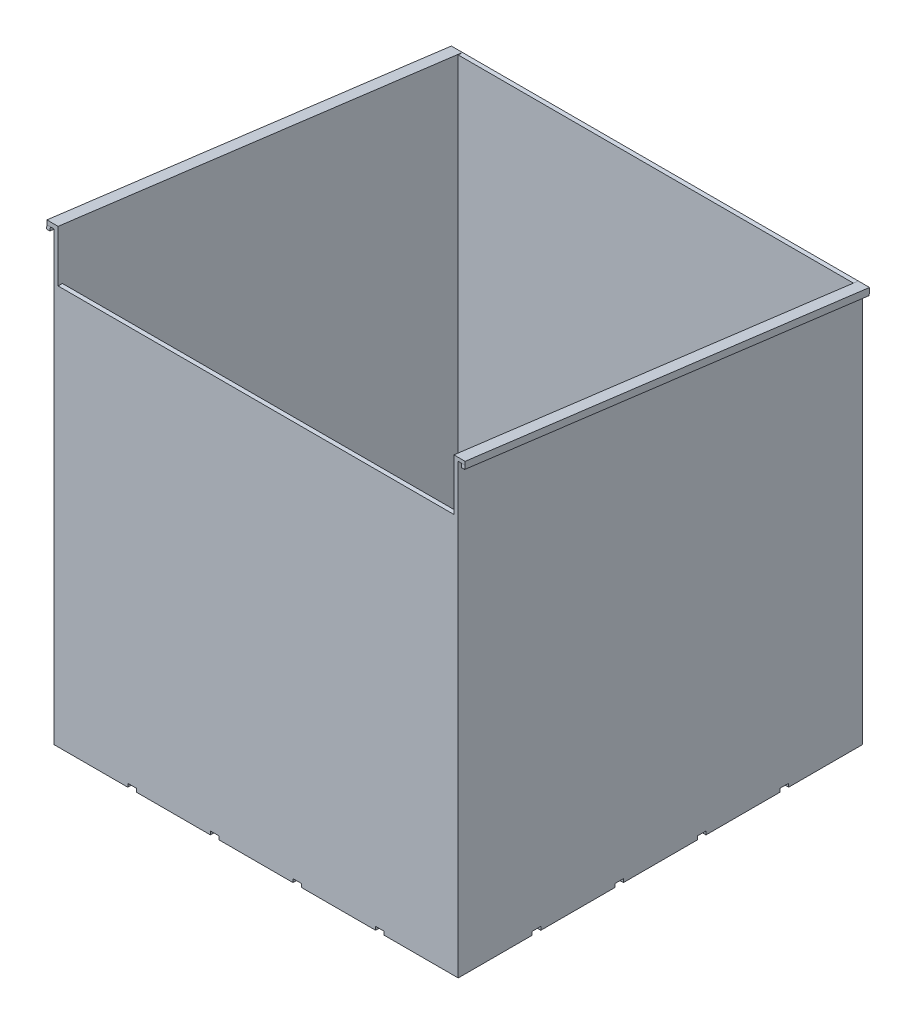
SolidWorks part; units mm, degrees
ref_plane "Front Plane" through (0, 0, 0) normal (0, 0, 1) x (1, 0, 0)
ref_plane "Top Plane" through (0, 0, 0) normal (0, 1, 0) x (1, 0, 0)
ref_plane "Right Plane" through (0, 0, 0) normal (1, 0, 0) x (0, 0, -1)
sketch "Sketch1" plane through (0, 0, 0) normal (0, 1, 0) x (1, 0, 0)
  line L1 (0, 0) -> (230, 0)
  line L2 (0, 0) -> (0, 230)
  line L3 (0, 230) -> (230, 230)
  line L4 (230, 0) -> (230, 230)
  dimension "D1" = 230
  dimension "D2" = 230
extrude "Extrude-Thin1" add sketch "Sketch1" along normal blind 230 thin contours L2 L3 L4 L1
sketch "Sketch4" plane through (232.5, 0, 0) normal (1, 0, 0) x (0, 0, -1)
  line L0 (-2.5, 230) -> (-2.5, 260)
  line L1 (-2.5, 260) -> (232.5, 230)
  line L2 (232.5, 230) -> (-2.5, 230)
  dimension "D1" = 30
extrude "Boss-Extrude1" add sketch "Sketch4" against normal blind 2.5 contours L1 L2 L0
sketch "Sketch5" plane through (-2.5, 0, 0) normal (-1, 0, 0) x (0, 0, 1)
  line L3 (-232.5, 230) -> (2.5, 230)
  line L4 (2.5, 230) -> (2.5, 260)
  line L5 (2.5, 260) -> (-232.5, 230)
  dimension "D1" = 30
extrude "Boss-Extrude2" add sketch "Sketch5" against normal blind 2.5 contours L5 L3 L4
sketch "Sketch6" plane through (-2.5, 0, 0) normal (-1, 0, 0) x (0, 0, 1)
  line L0 (-232.5, 230) -> (2.5, 260)
  line L1 (2.5, 260) -> (2.5, 257.5)
  line L2 (2.5, 257.5) -> (2.5, 0) construction
  line L3 (2.5, 257.5) -> (-232.5, 227.5)
  line L4 (-232.5, 227.5) -> (-232.5, 0) construction
  line L5 (-232.5, 227.5) -> (-232.5, 230)
  dimension "D1" = 2.5
extrude "Boss-Extrude5" add sketch "Sketch6" along normal blind 4 contours L0 L1 L3 L5
sketch "Sketch8" plane through (0, 253.0568, -32.3051) normal (0, -0.9919, 0.1266) x (1, 0, 0)
  line L0 (-6.5, -201.8196) -> (-6.5, 35.0876)
  line L1 (-6.5, 35.0876) -> (-4.5, 35.0876)
  line L2 (-4.5, 35.0876) -> (-2.5, 35.0876) construction
  line L3 (-4.5, 35.0876) -> (-4.5, -201.8196)
  line L4 (-6.5, -201.8196) -> (-2.5, -201.8196) construction
  line L5 (-4.5, -201.8196) -> (-6.5, -201.8196)
extrude "Boss-Extrude6" add sketch "Sketch8" along normal blind 2 contours L0 L1 L3 L5
sketch "Sketch9" plane through (232.5, 0, 0) normal (1, 0, 0) x (0, 0, -1)
  line L0 (-2.5, 260) -> (232.5, 230)
  line L1 (232.5, 230) -> (232.5, 228)
  line L2 (232.5, 228) -> (232.5, 0) construction
  line L3 (232.5, 228) -> (-2.5, 258)
  line L4 (-2.5, 258) -> (-2.5, 0) construction
  line L5 (-2.5, 258) -> (-2.5, 260)
  dimension "D1" = 2
extrude "Boss-Extrude7" add sketch "Sketch9" along normal blind 4 contours L0 L1 L3 L5
sketch "Sketch10" plane through (0, 253.5488, -32.3679) normal (0, -0.9919, 0.1266) x (1, 0, 0)
  line L0 (236.5, 35.1509) -> (236.5, -201.7563)
  line L1 (236.5, -201.7563) -> (234.5, -201.7563)
  line L2 (236.5, -201.7563) -> (232.5, -201.7563) construction
  line L3 (234.5, -201.7563) -> (234.5, 35.1509)
  line L4 (234.5, 35.1509) -> (236.5, 35.1509)
extrude "Boss-Extrude8" add sketch "Sketch10" along normal blind 2
sketch "Sketch11" plane through (0, 253.5488, -32.3679) normal (0, -0.9919, 0.1266) x (1, 0, 0)
  line L0 (232.5, -201.7563) -> (234.5, -201.7563)
  line L1 (234.5, -201.7563) -> (234.5, -199.7563)
  line L2 (234.5, 35.1509) -> (234.5, -199.7563) construction
  line L3 (234.5, -199.7563) -> (232.5, -199.7563)
  line L4 (232.5, -199.7563) -> (232.5, 35.1509) construction
  line L5 (232.5, -199.7563) -> (232.5, -201.7563)
  dimension "D1" = 2
  dimension "D2" = 2
extrude "Boss-Extrude9" add sketch "Sketch11" along normal blind 2 contours L3 L5 L0 L1
sketch "Sketch12" plane through (0, 253.0568, -32.3051) normal (0, -0.9919, 0.1266) x (1, 0, 0)
  line L0 (-2.5, -201.8196) -> (-2.5, -199.8196)
  line L1 (-2.5, 35.0876) -> (-2.5, -199.8196) construction
  line L2 (-4.5, -201.8196) -> (-2.5, -201.8196) construction
  line L3 (-2.5, -199.8196) -> (-4.5, -199.8196)
  line L4 (-4.5, 35.0876) -> (-4.5, -199.8196) construction
  line L5 (-4.5, -199.8196) -> (-4.5, -201.8196)
  line L6 (-4.5, -201.8196) -> (-2.5, -201.8196)
  dimension "D1" = 2
  dimension "D2" = 2
extrude "Boss-Extrude10" add sketch "Sketch12" along normal blind 2 contours L6 L0 L3 L5
sketch "Sketch13" plane through (0, 0, 0) normal (0, -1, 0) x (1, 0, 0)
  line L0 (-2.5, 2.5) -> (40.5, 2.5)
  line L1 (-2.5, 2.5) -> (232.5, 2.5) construction
  line L2 (40.5, 2.5) -> (40.5, -4.3411)
  line L3 (40.5, -4.3411) -> (45.5, -4.3411)
  line L4 (45.5, -4.3411) -> (45.5, 2.5)
  line L5 (45.5, 2.5) -> (88.5, 2.5)
  line L6 (88.5, 2.5) -> (88.5, -4.3411)
  line L7 (88.5, -4.3411) -> (93.5, -4.3411)
  line L8 (93.5, -4.3411) -> (93.5, 2.5)
  line L9 (93.5, 2.5) -> (136.5, 2.5)
  line L10 (136.5, 2.5) -> (136.5, -4.3411)
  line L11 (136.5, -4.3411) -> (141.5, -4.3411)
  line L12 (141.5, -4.3411) -> (141.5, 2.5)
  line L13 (141.5, 2.5) -> (184.5, 2.5)
  line L14 (184.5, 2.5) -> (184.5, -4.3411)
  line L15 (184.5, -4.3411) -> (189.5, -4.3411)
  line L16 (189.5, -4.3411) -> (189.5, 2.5)
  line L17 (189.5, 2.5) -> (232.5, 2.5)
  line L18 (232.5, -232.5) -> (189.5, -232.5)
  line L19 (189.5, -232.5) -> (189.5, -225.6589)
  line L20 (189.5, -225.6589) -> (184.5, -225.6589)
  line L21 (184.5, -225.6589) -> (184.5, -232.5)
  line L22 (184.5, -232.5) -> (141.5, -232.5)
  line L23 (141.5, -232.5) -> (141.5, -225.6589)
  line L24 (141.5, -225.6589) -> (136.5, -225.6589)
  line L25 (136.5, -225.6589) -> (136.5, -232.5)
  line L26 (136.5, -232.5) -> (93.5, -232.5)
  line L27 (93.5, -232.5) -> (93.5, -225.6589)
  line L28 (93.5, -225.6589) -> (88.5, -225.6589)
  line L29 (88.5, -225.6589) -> (88.5, -232.5)
  line L30 (88.5, -232.5) -> (45.5, -232.5)
  line L31 (45.5, -232.5) -> (45.5, -225.6589)
  line L32 (45.5, -225.6589) -> (40.5, -225.6589)
  line L33 (40.5, -225.6589) -> (40.5, -232.5)
  line L34 (40.5, -232.5) -> (-2.5, -232.5)
  line L35 (-2.5, -232.5) -> (232.5, -232.5) construction
  line L36 (232.5, 2.5) -> (232.5, -232.5) construction
  line L37 (-2.5, -232.5) -> (-2.5, -189.5)
  line L38 (-2.5, -189.5) -> (4.3411, -189.5)
  line L39 (4.3411, -189.5) -> (4.3411, -184.5)
  line L40 (4.3411, -184.5) -> (-2.5, -184.5)
  line L41 (-2.5, -184.5) -> (-2.5, -141.5)
  line L42 (-2.5, -141.5) -> (4.3411, -141.5)
  line L43 (4.3411, -141.5) -> (4.3411, -136.5)
  line L44 (4.3411, -136.5) -> (-2.5, -136.5)
  line L45 (-2.5, -136.5) -> (-2.5, -93.5)
  line L46 (-2.5, -93.5) -> (4.3411, -93.5)
  line L47 (4.3411, -93.5) -> (4.3411, -88.5)
  line L48 (4.3411, -88.5) -> (-2.5, -88.5)
  line L49 (-2.5, -88.5) -> (-2.5, -45.5)
  line L50 (-2.5, -45.5) -> (4.3411, -45.5)
  line L51 (4.3411, -45.5) -> (4.3411, -40.5)
  line L52 (4.3411, -40.5) -> (-2.5, -40.5)
  line L53 (-2.5, -40.5) -> (-2.5, 2.5)
  line L54 (232.5, 2.5) -> (232.5, -40.5)
  line L55 (232.5, -40.5) -> (225.6589, -40.5)
  line L56 (225.6589, -40.5) -> (225.6589, -45.5)
  line L57 (225.6589, -45.5) -> (232.5, -45.5)
  line L58 (232.5, -45.5) -> (232.5, -88.5)
  line L59 (232.5, -88.5) -> (225.6589, -88.5)
  line L60 (225.6589, -88.5) -> (225.6589, -93.5)
  line L61 (225.6589, -93.5) -> (232.5, -93.5)
  line L62 (232.5, -93.5) -> (232.5, -136.5)
  line L63 (232.5, -136.5) -> (225.6589, -136.5)
  line L64 (225.6589, -136.5) -> (225.6589, -141.5)
  line L65 (225.6589, -141.5) -> (232.5, -141.5)
  line L66 (232.5, -141.5) -> (232.5, -184.5)
  line L67 (232.5, -184.5) -> (225.6589, -184.5)
  line L68 (225.6589, -184.5) -> (225.6589, -189.5)
  line L69 (225.6589, -189.5) -> (232.5, -189.5)
  line L70 (232.5, -189.5) -> (232.5, -232.5)
  dimension "D1" = 5
  dimension "D2" = 5
  dimension "D3" = 5
  dimension "D4" = 5
  dimension "D5" = 5
  dimension "D6" = 5
  dimension "D7" = 5
  dimension "D8" = 5
  dimension "D9" = 43
  dimension "D10" = 5
  dimension "D11" = 5
  dimension "D12" = 5
  dimension "D13" = 5
  dimension "D14" = 5
  dimension "D15" = 5
  dimension "D16" = 5
  dimension "D17" = 5
extrude "Boss-Extrude11" add sketch "Sketch13" along normal blind 2 contours L50 L51 L52 L53 L0 L2 L3 L4 L5 L6 L7 L8 L9 L10 L11 L12 L13 L14 L15 L16 L17 L54 L55 L56 L57 L58 L59 L60 L61 L62 L63 L64 L65 L66 L67 L68 L69 L70 L18 L19 L20 L21 L22 L23 L24 L25 L26 L27 L28 L29 L30 L31 L32 L33 L34 L37 L38 L39 L40 L41 L42 L43 L44 L45 L46 L47 L48 L49
